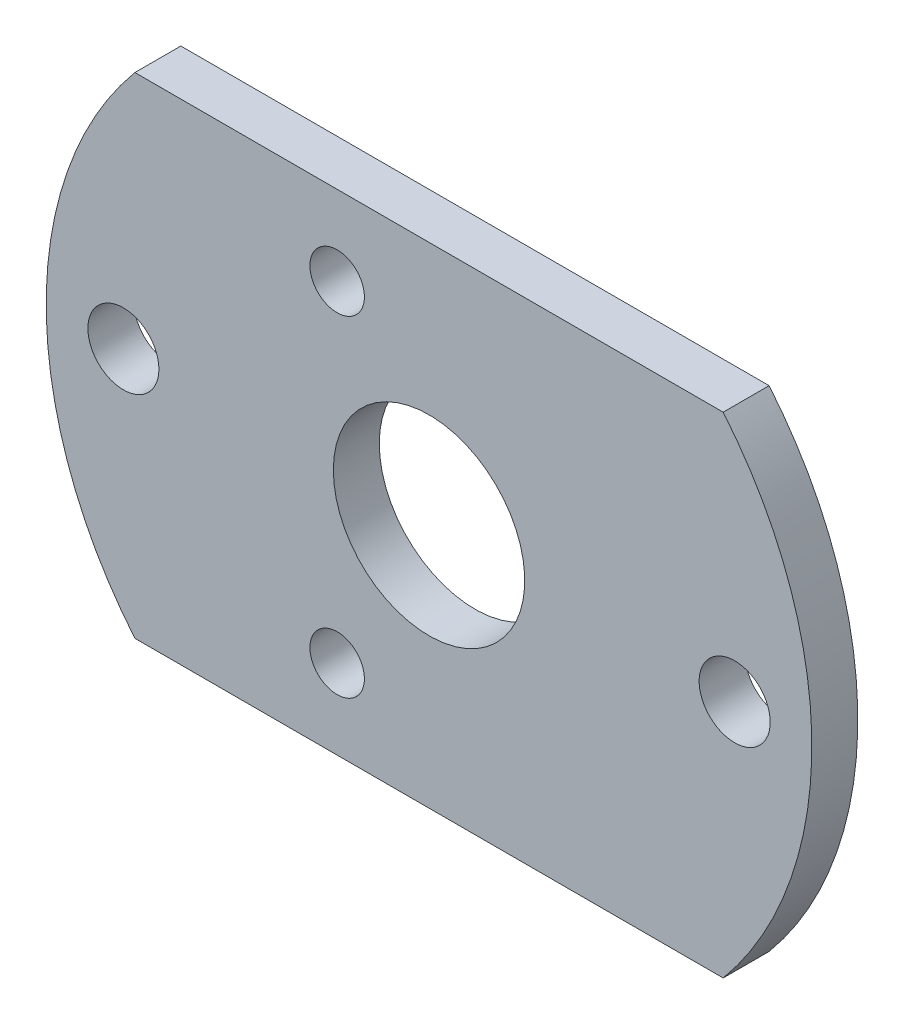
SolidWorks part; units mm, degrees
material "Cast Alloy Steel"
ref_plane "Front Plane" through (0, 0, 0) normal (0, 0, 1) x (1, 0, 0)
ref_plane "Top Plane" through (0, 0, 0) normal (0, 1, 0) x (1, 0, 0)
ref_plane "Right Plane" through (0, 0, 0) normal (1, 0, 0) x (0, 0, -1)
sketch "Sketch1" plane through (0, 0, 0) normal (0, 0, 1) x (1, 0, 0)
  circle A0 centre (0, 0) radius 15.875
  circle A1 centre (0, 0) radius 3.9688
  dimension "D1" = 7.9375
  dimension "D2" = 31.75
extrude "Boss-Extrude1" add sketch "Sketch1" along normal blind 1.905
hole_wizard "MotorClearanceHoles" positions "Sketch5" profile "Sketch4" hole size "#4" standard "ANSI Inch" end condition through all
sketch "Sketch5" plane through (0, 0, 1.905) normal (0, 0, 1) x (1, 0, 0)
  line L0 (0, 0) -> (0, 12.3097) construction
  point P0 (-12.6746, 0)
  point P2 (12.6746, 0)
  dimension "D1" = 25.3492
sketch "Sketch4" plane through (-12.6746, 0, 1.905) normal (1, 0, 0) x (0, -1, 0)
  line L0 (0, 0) -> (0, 1.905)
  line L1 (0, 1.905) -> (1.4732, 1.905)
  line L2 (1.4732, 1.905) -> (1.4732, 0)
  line L5 (1.4732, 0) -> (0, 0)
  line L11 (0, -6.35) -> (0, 107.95) construction
  dimension "Thru Hole Dia." = 2.9464
  dimension "Thru Hole Depth" = 1.905
hole_wizard "EncoderSetScrews" positions "Sketch7" profile "Sketch6" tap size "#4-40" standard "ANSI Inch" end condition through all
sketch "Sketch7" plane through (0, 0, 1.905) normal (0, 0, 1) x (1, 0, 0)
  line L0 (-21.019, 0) -> (-19.6675, 0) construction
  point P0 (-3.81, 6.858)
  point P2 (-3.81, -6.858)
  dimension "D1" = 13.716
  dimension "D2" = 3.81
sketch "Sketch6" plane through (-3.81, 6.858, 1.905) normal (1, 0, 0) x (0, -1, 0)
  line L0 (0, 0) -> (0, 1.905)
  line L1 (0, 1.905) -> (1.1303, 1.905)
  line L2 (1.1303, 1.905) -> (1.1303, 0)
  line L5 (1.1303, 0) -> (0, 0)
  line L11 (0, -6.35) -> (0, 107.95) construction
  dimension "Thru Tap Drill Dia." = 2.2606
  dimension "Thru Tap Drill Depth" = 1.905
cosmetic thread "Hole Thread1" parameters "D2"=2.8448
cosmetic thread "Hole Thread2" parameters "D2"=2.8448
sketch "Sketch8" plane through (0, 0, 1.905) normal (0, 0, 1) x (1, 0, 0)
  line L0 (-12.198, -10.16) -> (12.198, -10.16)
  line L1 (0, 0) -> (-29.8268, 0) construction
  line L2 (-12.198, 10.16) -> (12.198, 10.16)
  arc A0 (-12.198, 10.16) -> (12.198, 10.16) centre (0, 0) cw
  circle A1 centre (0, 0) radius 15.875
  arc A2 (-12.198, -10.16) -> (12.198, -10.16) centre (0, 0) ccw
  dimension "D2" = 10.16
  dimension "D1" = 0
extrude "LinActCutaway" cut sketch "Sketch8" against normal through all
